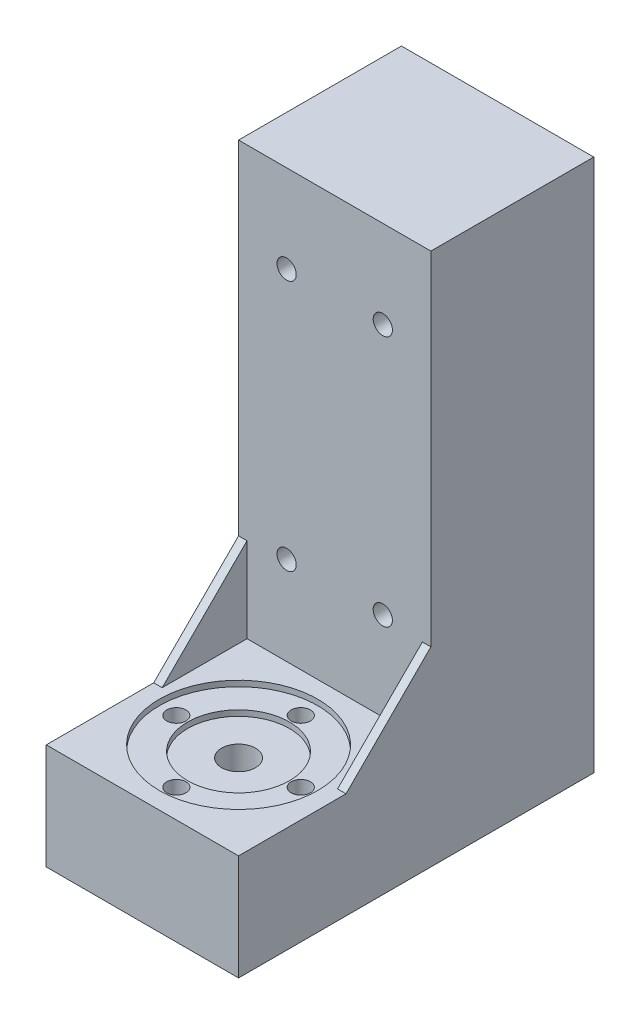
SolidWorks part; units mm, degrees
material "ABS"
ref_plane "Front Plane" through (0, 0, 0) normal (0, 0, 1) x (1, 0, 0)
ref_plane "Top Plane" through (0, 0, 0) normal (0, 1, 0) x (1, 0, 0)
ref_plane "Right Plane" through (0, 0, 0) normal (1, 0, 0) x (0, 0, -1)
sketch "Sketch1" plane through (0, 0, 0) normal (1, 0, 0) x (0, 0, -1)
  line L0 (0, 0) -> (62.8, 0)
  line L1 (62.8, 0) -> (62.8, 94.3)
  line L2 (62.8, 94.3) -> (34, 94.3)
  line L3 (34, 94.3) -> (34, 18.7)
  line L4 (34, 18.7) -> (0, 18.7)
  line L5 (0, 18.7) -> (0, 0)
  line L6 (34, 18.7) -> (62.8, 18.7) construction
  line L7 (34, 18.7) -> (34, 0) construction
  dimension "D1" = 75.6
  dimension "D2" = 18.7
  dimension "D3" = 94.3
  dimension "D4" = 28.8
  dimension "D5" = 34
extrude "Boss-Extrude1" add sketch "Sketch1" along normal mid plane 34
sketch "Sketch2" plane through (0, 0, -34) normal (0, 0, 1) x (1, 0, 0)
  line L0 (0, 0) -> (0, 34.35) construction
  line L1 (0, 94.3) -> (0, 78.8) construction
  line L2 (17, 94.3) -> (-17, 94.3) construction
  line L4 (0, 78.8) -> (8.5, 78.8) construction
  line L5 (0, 34.35) -> (8.5, 34.35) construction
  circle A0 centre (8.5, 34.35) radius 1.7
  circle A1 centre (8.5, 78.8) radius 1.7
  circle A2 centre (-8.5, 34.35) radius 1.7
  circle A3 centre (-8.5, 78.8) radius 1.7
  dimension "D4" = 3.4
  dimension "D5" = 3.4
  dimension "D1" = 34.35
  dimension "D2" = 15.5
  dimension "D3" = 8.5
extrude "Cut-Extrude1" cut sketch "Sketch2" against normal through all
sketch "Sketch5" plane through (0, 18.7, 0) normal (0, 1, 0) x (1, 0, 0)
  line L0 (17, 17) -> (-17, 17) construction
  line L1 (17, 34) -> (17, 0) construction
  line L2 (-17, 34) -> (-17, 0) construction
  circle A0 centre (0, 17) radius 14
  dimension "D1" = 28
extrude "Cut-Extrude3" cut sketch "Sketch5" against normal blind 1
sketch "Sketch4" plane through (0, 18.7, 0) normal (0, 1, 0) x (1, 0, 0)
  line L0 (17, 17) -> (-17, 17) construction
  line L1 (17, 34) -> (17, 0) construction
  line L2 (-17, 34) -> (-17, 0) construction
  circle A0 centre (0, 17) radius 9
  dimension "D1" = 18
extrude "Cut-Extrude2" cut sketch "Sketch4" against normal blind 2
sketch "Sketch6" plane through (0, 17.7, 0) normal (0, 1, 0) x (1, 0, 0)
  line L0 (0, 17) -> (0, 6) construction
  circle A0 centre (0, 6) radius 1.7
  circle A1 centre (0, 17) radius 11 construction
  circle A2 centre (0, 28) radius 1.7
  circle A3 centre (11, 17) radius 1.7
  circle A4 centre (-11, 17) radius 1.7
  circle A5 centre (0, 17) radius 3
  dimension "D2" = 3.4
  dimension "D1" = 22
  dimension "D3" = 3.4
  dimension "D4" = 3.4
  dimension "D5" = 3.4
  dimension "D6" = 6
extrude "Cut-Extrude4" cut sketch "Sketch6" against normal through all
sketch "Sketch8" plane through (17, 0, 0) normal (1, 0, 0) x (0, 0, -1)
  line L0 (34, 18.7) -> (34, 33.7)
  line L1 (34, 94.3) -> (34, 18.7) construction
  line L2 (34, 33.7) -> (19, 18.7)
  line L3 (34, 18.7) -> (0, 18.7) construction
  line L4 (19, 18.7) -> (34, 18.7)
  dimension "D1" = 15
  dimension "D2" = 15
extrude "Boss-Extrude2" add sketch "Sketch8" against normal blind 1.5
sketch "Sketch9" plane through (-17, 0, 0) normal (-1, 0, 0) x (0, 0, 1)
  line L0 (-34, 18.7) -> (-19, 18.7)
  line L1 (-19, 18.7) -> (-34, 33.7)
  line L2 (-34, 33.7) -> (-34, 18.7)
extrude "Boss-Extrude3" add sketch "Sketch9" against normal blind 1.5 separate body
